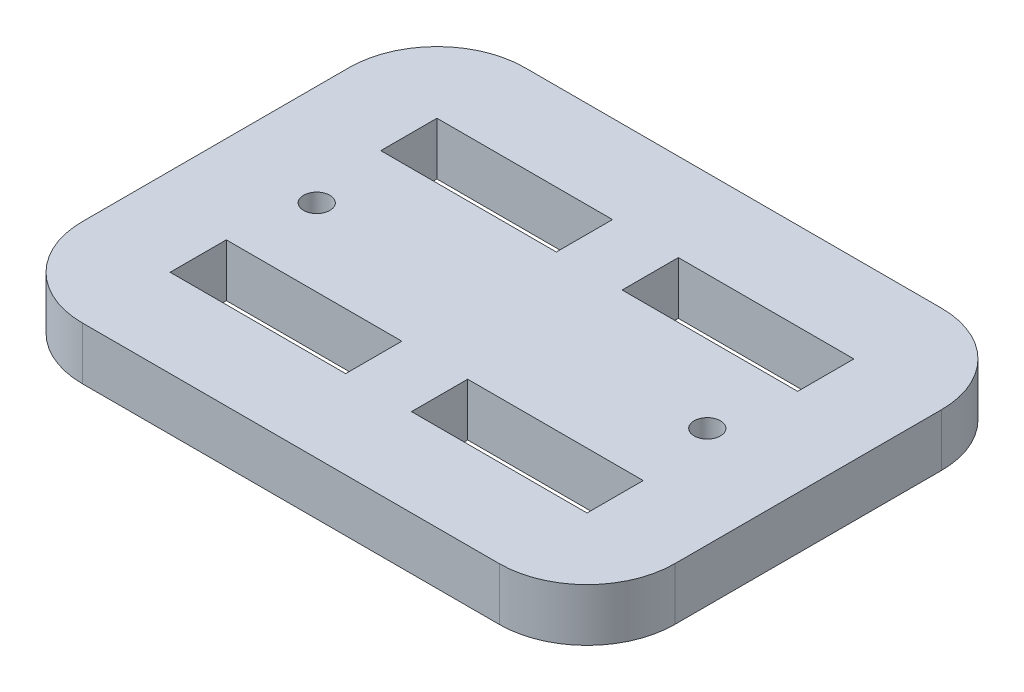
SolidWorks part; units mm, degrees
ref_plane "Front Plane" through (0, 0, 0) normal (0, 0, 1) x (1, 0, 0)
ref_plane "Top Plane" through (0, 0, 0) normal (0, 1, 0) x (1, 0, 0)
ref_plane "Right Plane" through (0, 0, 0) normal (1, 0, 0) x (0, 0, -1)
sketch "Sketch1" plane through (0, 0, 0) normal (0, 1, 0) x (1, 0, 0)
  line L0 (-20.75, 0) -> (0, 0) construction
  line L1 (-33.75, 25.2) -> (0, 25.2)
  line L2 (-33.75, 25.2) -> (-33.75, -25.2)
  line L3 (-33.75, 0) -> (-23.75, 0) construction
  line L4 (0, 25.2) -> (0, -25.2)
  line L5 (-33.75, 25.2) -> (0, 0) construction
  line L6 (-33.75, 0) -> (0, 25.2) construction
  line L7 (-23.75, 15.2) -> (-3.75, 15.2)
  line L8 (-23.75, 15.2) -> (-23.75, 8.8)
  line L9 (-23.75, 8.8) -> (-3.75, 8.8)
  line L10 (-3.75, 15.2) -> (-3.75, 8.8)
  line L11 (-23.75, 15.2) -> (-3.75, 8.8) construction
  line L12 (-23.75, 8.8) -> (-3.75, 15.2) construction
  line L13 (-23.75, -8.8) -> (-3.75, -15.2) construction
  line L14 (-23.75, -15.2) -> (-3.75, -8.8) construction
  line L15 (-33.75, 0) -> (0, -25.2) construction
  line L16 (-33.75, -25.2) -> (0, 0) construction
  line L17 (-3.75, -15.2) -> (-3.75, -8.8)
  line L18 (-23.75, -8.8) -> (-3.75, -8.8)
  line L19 (-23.75, -15.2) -> (-23.75, -8.8)
  line L20 (-23.75, -15.2) -> (-3.75, -15.2)
  line L21 (-33.75, -25.2) -> (0, -25.2)
  circle A0 centre (-22.25, 0) radius 1.5
  point P0 (-16.875, 12.6)
  point P6 (-13.75, 12)
  point P21 (-13.75, -12)
  point P22 (-16.875, -12.6)
  dimension "D1" = 1.5
  dimension "D2" = 6.4
  dimension "D3" = 20
  dimension "D4" = 3.75
  dimension "D5" = 12
  dimension "D6" = 10
  dimension "D7" = 10
  dimension "D8" = 22.25
extrude "Boss-Extrude1" add sketch "Sketch1" along normal blind 6
fillet "Fillet1" radius 10 2 edges at (-33.75, 3, -25.2) (-33.75, 3, 25.2)
mirror "Mirror1" about plane through (0, 6, -25.2) normal (-1, 0, 0) of "Fillet1", "Boss-Extrude1"
equation "\"housing_t\"= \"housing_t_glob@troublemaker.Assembly\""
equation "\"M3_d\"= \"M3_d_laser@troublemaker.Assembly\""
equation "\"D1@Sketch1\"=\"M3_d\" / 2"
equation "\"D2@Sketch1\"=\"housing_t\" + 0.4"
equation "\"D5@Sketch1\"=2 * \"housing_t\""
equation "\"D1@Boss-Extrude1\"=\"housing_t\""
